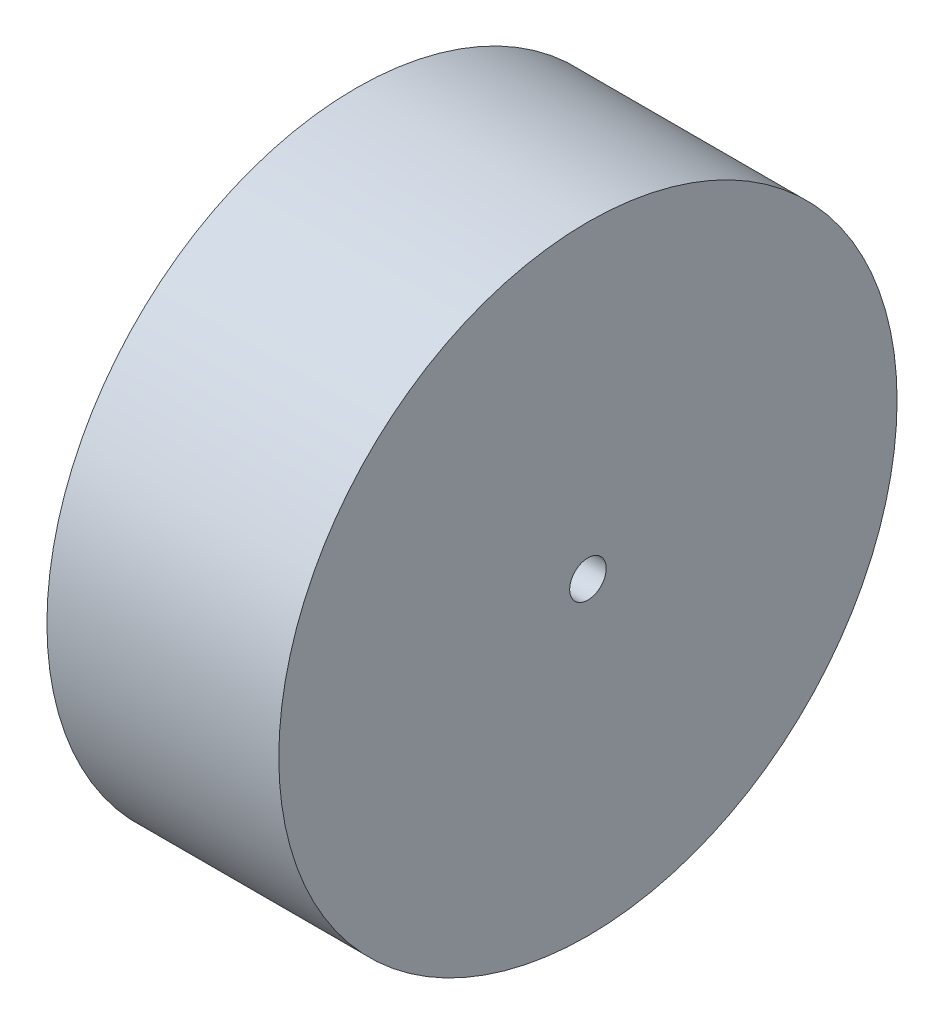
SolidWorks part; units mm, degrees
material "Polyurethane Foam Flexible"
ref_plane "Front Plane" through (0, 0, 0) normal (0, 0, 1) x (1, 0, 0)
ref_plane "Top Plane" through (0, 0, 0) normal (0, 1, 0) x (1, 0, 0)
ref_plane "Right Plane" through (0, 0, 0) normal (1, 0, 0) x (0, 0, -1)
sketch "Sketch1" plane through (0, 0, 0) normal (1, 0, 0) x (0, 0, -1)
  circle A0 centre (0, 0) radius 25.4
  circle A1 centre (0, 0) radius 1.5
  dimension "D1" = 50.8
  dimension "D2" = 3
extrude "Boss-Extrude2" add sketch "Sketch1" along normal blind 19.05
